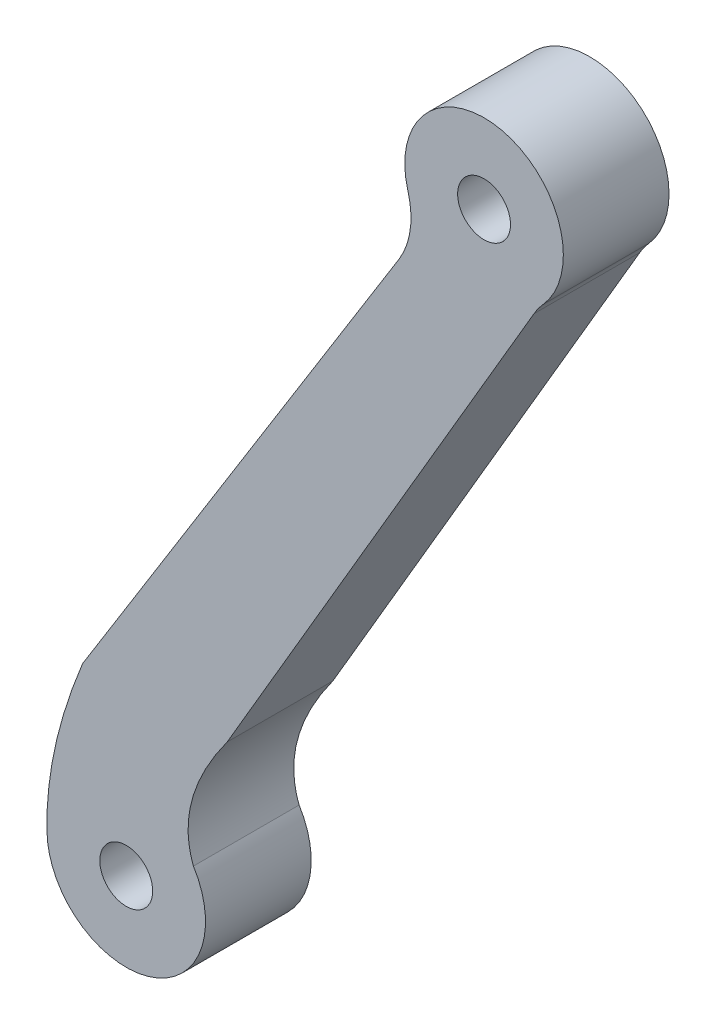
SolidWorks part; units mm, degrees
ref_plane "Спереди" through (0, 0, 0) normal (0, 0, 1) x (1, 0, 0)
ref_plane "Сверху" through (0, 0, 0) normal (0, 1, 0) x (1, 0, 0)
ref_plane "Справа" through (0, 0, 0) normal (1, 0, 0) x (0, 0, -1)
sketch "Sketch5" plane through (0, 0, 0) normal (0, 0, 1) x (1, 0, 0)
  line L0 (1.7523, 0.4742) -> (37.3029, 86.8114) construction
  line L1 (-1.0106, -0.6044) -> (29.6618, 87.5839) construction
  line L2 (0, 0) -> (17.8901, 43.1295)
  line L3 (0, 0) -> (114.3643, 0) construction
  line L4 (23.8823, 39.6684) -> (24.5035, 51.2503)
  line B0 (17.4507, 115.16) -> (29.9551, 112.6983)
  spline B1 degree 3 poles (29.9551, 112.6983) (28.321, 116.0983) (27.9284, 121.1676) (30.1713, 134.4746) (29.8473, 132.0116) (30.6222, 139.9349) (27.0176, 140.9027) knots 0 0 0 0 0.297085 0.369784 0.687298 1 1 1 1
  spline B2 degree 2 poles (27.0176, 140.9027) (20.5603, 128.6427) (17.4507, 115.16) knots 0 0 0 1 1 1
  spline B3 degree 2 poles (27.0176, 140.9027) (26.5004, 134.6878) (22.2537, 130.5645) knots 0 0 0 1 1 1
  line B4 (17.1977, 114.3508) -> (29.842, 112.2111)
  line B5 (28.7001, 84.8969) -> (10.3668, 87.513)
  spline B6 degree 1 poles (17.1977, 114.3508) (10.3668, 87.513) knots 0 0 1 1
  spline B7 degree 2 poles (29.842, 112.2111) (22.5534, 98.8452) (28.7001, 84.8969) knots 0 0 0 1 1 1
  line B8 (10.1904, 87.4159) -> (28.2572, 84.4958)
  line B9 (32.8909, 45.7292) -> (10.0695, 42.8593)
  spline B10 degree 2 poles (10.1904, 87.4159) (10.0234, 65.1379) (10.0695, 42.8593) knots 0 0 0 1 1 1
  spline B11 degree 2 poles (28.2572, 84.4958) (20.6417, 64.1094) (32.8909, 45.7292) knots 0 0 0 1 1 1
  line B12 (10.2797, 36.8758) -> (3.9253, -13.9853)
  line B13 (3.9253, -13.9853) -> (33.9594, -31.0804)
  line B14 (33.9594, -31.0804) -> (45.9193, -27.7969)
  line B15 (45.9193, -27.7969) -> (58.2918, -13.9853)
  line B16 (58.2918, -13.9853) -> (69.0331, -4.9875)
  line B17 (69.0331, -4.9875) -> (82.514, 2.0236)
  line B18 (82.514, 2.0236) -> (89.2736, 3.8794)
  line B19 (89.2736, 3.8794) -> (92.4846, 9.5208)
  line B20 (92.4846, 9.5208) -> (96.8914, 17.263)
  line B21 (96.8914, 17.263) -> (101.4978, 21.1217)
  line B22 (101.4978, 21.1217) -> (103.9241, 23.1541)
  line B23 (104.261, 27.4157) -> (104.5375, 25.5318)
  line B24 (84.192, 21.2056) -> (87.7484, 22.7822)
  line B25 (87.7484, 22.7822) -> (92.912, 27.4956)
  line B26 (71.6086, 15.6268) -> (84.192, 21.2056)
  line B27 (92.912, 27.4956) -> (95.357, 29.7274)
  line B28 (95.357, 29.7274) -> (96.8049, 29.9399)
  line B29 (71.6086, 15.6268) -> (53.4239, 15.2713)
  line B30 (48.0904, 17.5622) -> (39.9394, 26.4919)
  line B31 (39.9394, 26.4919) -> (33.9594, 37.99)
  line B32 (33.9594, 37.99) -> (10.2797, 36.8758)
  line B33 (96.8049, 29.9399) -> (99.4078, 30.2175)
  line B34 (99.4078, 30.2175) -> (102.2786, 29.261)
  line B35 (102.2786, 29.261) -> (104.261, 27.4157)
  line B36 (104.5375, 25.5318) -> (103.9241, 23.1541)
  arc B37 (53.4239, 15.2713) -> (48.0904, 17.5622) centre (53.2864, 22.3051) cw
  spline B38 degree 3 poles (104.261, 27.4157) (103.5289, 27.0494) (99.8378, 26.2685) (94.8982, 17.2338) (98.6516, 18.7375) knots 0 0 0 0 0.441207 1 1 1 1
  line B39 (27.7375, 116.5129) -> (14.1959, 87.8955)
  line B40 (27.7375, 116.5129) -> (25.9485, 114.8372)
  line B41 (25.9485, 114.8372) -> (27.5763, 114.067)
  line B42 (27.7375, 116.5129) -> (27.5763, 114.067)
  line B43 (26.1527, 88.0864) -> (17.8901, 43.1295)
  line B44 (19.3622, 85.005) -> (23.8823, 39.6684)
  line B45 (19.3622, 85.005) -> (17.7584, 73.9508)
  line B46 (17.7584, 73.9508) -> (23.117, 74.485)
  line B47 (23.117, 74.485) -> (19.3622, 85.005)
  line B48 (26.1527, 88.0864) -> (23.7481, 82.7635)
  line B49 (23.7481, 82.7635) -> (25.1278, 82.5099)
  line B50 (25.1278, 82.5099) -> (26.5087, 82.2561)
  line B51 (26.5087, 82.2561) -> (26.1527, 88.0864)
  line B52 (26.1527, 88.0864) -> (19.3622, 85.005)
  line B53 (19.3622, 85.005) -> (22.3683, 87.7853)
  line B54 (22.3683, 87.7853) -> (22.9012, 86.6109)
  line B55 (22.9012, 86.6109) -> (23.4998, 85.2917)
  line B56 (23.4998, 85.2917) -> (19.3622, 85.005)
  dimension "D1" = 93.37
  dimension "D2" = 93.37
  dimension "D4" = 67.471
  dimension "D5" = 8.764
sketch_block_instance "Block1-1"
sketch_block "Block1"
sketch_block_instance "Block2-1"
sketch_block "Block2"
sketch_block_instance "Block3-1"
sketch_block "Block3"
sketch_block_instance "Block18-1"
sketch_block "Block18"
sketch_block_instance "Block44-1"
sketch_block "Block44"
sketch_block_instance "Block46-1"
sketch_block "Block46"
sketch_block_instance "Block47-1"
sketch_block "Block47"
sketch_block_instance "Block48-1"
sketch_block "Block48"
sketch_block_instance "Block50-1"
sketch_block "Block50"
sketch "Sketch6" plane through (0, 0, 0) normal (0, 0, 1) x (1, 0, 0)
  line L0 (12.546, 94.0292) -> (24.519, 113.2669)
  line L5 (29.6287, 114.0374) -> (18.0165, 94.1948)
  line L6 (12.546, 94.0292) -> (11.1432, 90.6208) construction
  line L7 (11.1432, 90.6208) -> (11.1959, 87.8955) construction
  line L8 (18.0165, 94.1948) -> (15.9886, 91.4158) construction
  line L9 (15.9886, 91.4158) -> (16.739, 89.4869) construction
  arc A0 (29.9777, 114.5175) -> (29.6287, 114.0374) centre (32.218, 112.5222) ccw
  circle A1 centre (14.1959, 87.8955) radius 3
  circle A2 centre (27.7375, 116.5129) radius 1
  circle A3 centre (14.1959, 87.8955) radius 1
  arc A4 (29.9777, 114.5175) -> (24.8547, 115.6825) centre (27.7375, 116.5129) ccw
  arc A5 (24.519, 113.2669) -> (24.8547, 115.6825) centre (21.972, 114.8521) ccw
  spline S2 degree 2 poles (12.546, 94.0292) (11.1432, 90.6208) (11.1959, 87.8955) knots 0 0 0 1 1 1
  spline S3 degree 2 poles (18.0165, 94.1948) (15.9886, 91.4158) (16.739, 89.4869) knots 0 0 0 1 1 1
  dimension "D1" = 2
  dimension "D2" = 6
  dimension "D3" = 3
extrude "Boss-Extrude1" add sketch "Sketch6" along normal blind 4
